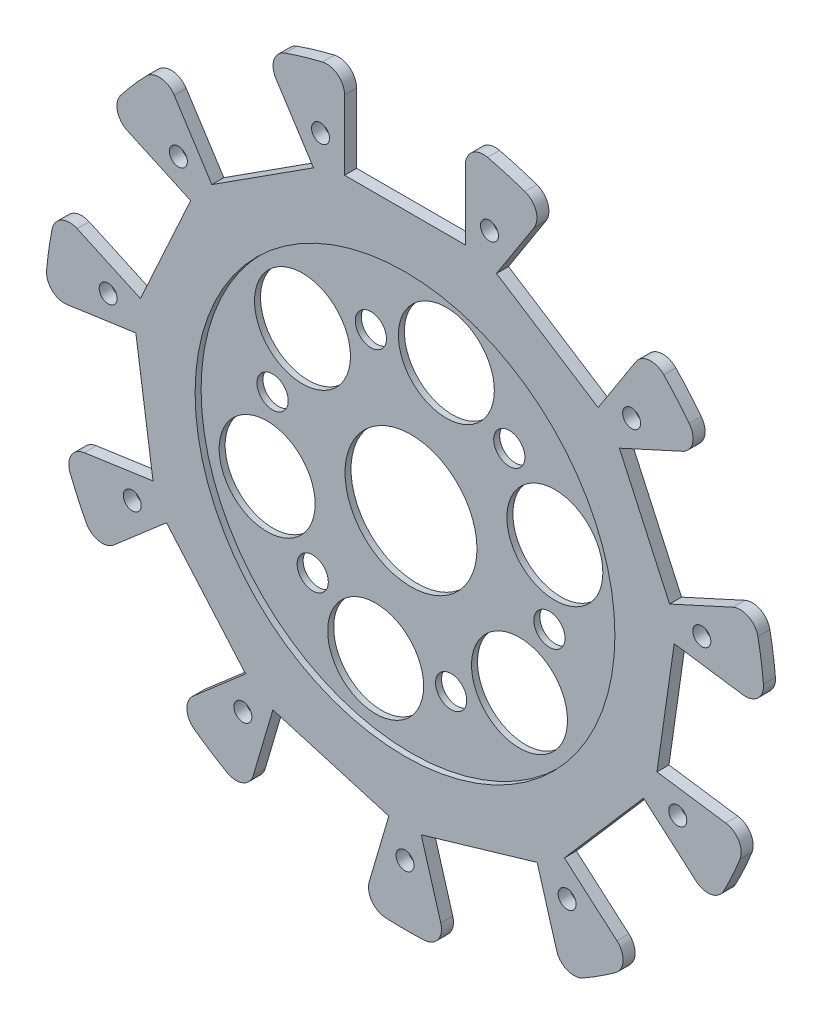
SolidWorks part; units mm, degrees
ref_plane "Front Plane" through (0, 0, 0) normal (0, 0, 1) x (1, 0, 0)
ref_plane "Top Plane" through (0, 0, 0) normal (0, 1, 0) x (1, 0, 0)
ref_plane "Right Plane" through (0, 0, 0) normal (1, 0, 0) x (0, 0, -1)
sketch "Sketch1" plane through (0, 0, 0) normal (0, 0, 1) x (1, 0, 0)
  line L44 (21.5207, 52.1193) -> (15.2567, 42.3722)
  line L47 (-10.0734, 55.4805) -> (-10.0734, 43.8941)
  line L48 (-10.0734, 43.8941) -> (10.0734, 43.8941)
  line L49 (10.0734, 55.4805) -> (10.0734, 43.8941)
  line L51 (38.4693, 41.2271) -> (32.2052, 31.48)
  line L52 (15.2567, 42.3722) -> (32.2052, 31.48)
  line L53 (46.2822, 32.2105) -> (35.7428, 27.3974)
  line L55 (54.6515, 13.8844) -> (44.1121, 9.0712)
  line L56 (35.7428, 27.3974) -> (44.1121, 9.0712)
  line L57 (56.3494, 2.0752) -> (44.8809, 3.7241)
  line L59 (53.4822, -17.8666) -> (42.0137, -16.2176)
  line L60 (44.8809, 3.7241) -> (42.0137, -16.2176)
  line L61 (48.526, -28.719) -> (39.7696, -21.1316)
  line L63 (35.3327, -43.945) -> (26.5763, -36.3575)
  line L64 (39.7696, -21.1316) -> (26.5763, -36.3575)
  line L65 (25.296, -50.3952) -> (22.0318, -39.2781)
  line L67 (5.9653, -56.0712) -> (2.701, -44.9541)
  line L68 (22.0318, -39.2781) -> (2.701, -44.9541)
  line L69 (-5.9653, -56.0712) -> (-2.701, -44.9541)
  line L71 (-25.296, -50.3952) -> (-22.0318, -39.2781)
  line L72 (-2.701, -44.9541) -> (-22.0318, -39.2781)
  line L73 (-35.3327, -43.945) -> (-26.5763, -36.3575)
  line L75 (-48.526, -28.719) -> (-39.7696, -21.1316)
  line L76 (-26.5763, -36.3575) -> (-39.7696, -21.1316)
  line L77 (-53.4822, -17.8666) -> (-42.0137, -16.2176)
  line L79 (-56.3494, 2.0752) -> (-44.8809, 3.7241)
  line L80 (-42.0137, -16.2176) -> (-44.8809, 3.7241)
  line L81 (-54.6515, 13.8844) -> (-44.1121, 9.0712)
  line L83 (-46.2822, 32.2105) -> (-35.7428, 27.3974)
  line L84 (-44.1121, 9.0712) -> (-35.7428, 27.3974)
  line L85 (-38.4693, 41.2271) -> (-32.2052, 31.48)
  line L87 (-21.5207, 52.1193) -> (-15.2567, 42.3722)
  line L88 (-32.2052, 31.48) -> (-15.2567, 42.3722)
  arc A33 (-43.1506, 41.6896) -> (-47.4063, 36.7783) centre (0, 0) ccw
  arc A34 (-13.7615, 58.4005) -> (-19.9968, 56.5697) centre (0, 0) ccw
  arc A35 (19.9968, 56.5697) -> (13.7615, 58.4005) centre (0, 0) ccw
  arc A36 (47.4063, 36.7783) -> (43.1506, 41.6896) centre (0, 0) ccw
  arc A37 (59.7646, 5.3101) -> (58.8397, 11.7426) centre (0, 0) ccw
  arc A38 (53.148, -27.844) -> (55.8476, -21.9327) centre (0, 0) ccw
  arc A39 (29.6574, -52.1578) -> (35.1243, -48.6444) centre (0, 0) ccw
  arc A40 (-3.2493, -59.912) -> (3.2493, -59.912) centre (0, 0) ccw
  arc A41 (-35.1243, -48.6444) -> (-29.6574, -52.1578) centre (0, 0) ccw
  arc A42 (-55.8476, -21.9327) -> (-53.148, -27.844) centre (0, 0) ccw
  arc A43 (-58.8397, 11.7426) -> (-59.7646, 5.3101) centre (0, 0) ccw
  arc A44 (-54.6515, 13.8844) -> (-58.8397, 11.7426) centre (-55.8977, 11.1555) ccw
  arc A45 (-56.3494, 2.0752) -> (-59.7646, 5.3101) centre (-56.7763, 5.0446) cw
  arc A46 (-48.526, -28.719) -> (-53.148, -27.844) centre (-50.4906, -26.4518) cw
  arc A47 (-53.4822, -17.8666) -> (-55.8476, -21.9327) centre (-53.0553, -20.836) ccw
  arc A48 (-25.296, -50.3952) -> (-29.6574, -52.1578) centre (-28.1745, -49.55) cw
  arc A49 (-35.3327, -43.945) -> (-35.1243, -48.6444) centre (-33.3681, -46.2122) ccw
  arc A50 (-5.9653, -56.0712) -> (-3.2493, -59.912) centre (-3.0868, -56.9164) ccw
  arc A51 (5.9653, -56.0712) -> (3.2493, -59.912) centre (3.0868, -56.9164) cw
  arc A52 (35.3327, -43.945) -> (35.1243, -48.6444) centre (33.3681, -46.2122) cw
  arc A53 (25.296, -50.3952) -> (29.6574, -52.1578) centre (28.1745, -49.55) ccw
  arc A54 (48.526, -28.719) -> (53.148, -27.844) centre (50.4906, -26.4518) ccw
  arc A55 (53.4822, -17.8666) -> (55.8476, -21.9327) centre (53.0553, -20.836) cw
  arc A56 (56.3494, 2.0752) -> (59.7646, 5.3101) centre (56.7763, 5.0446) ccw
  arc A57 (54.6515, 13.8844) -> (58.8397, 11.7426) centre (55.8977, 11.1555) cw
  arc A58 (46.2822, 32.2105) -> (47.4063, 36.7783) centre (45.036, 34.9394) ccw
  arc A59 (38.4693, 41.2271) -> (43.1506, 41.6896) centre (40.9931, 39.6052) cw
  arc A60 (21.5207, 52.1193) -> (19.9968, 56.5697) centre (18.997, 53.7412) ccw
  arc A61 (10.0734, 55.4805) -> (13.7615, 58.4005) centre (13.0734, 55.4805) cw
  arc A62 (-10.0734, 55.4805) -> (-13.7615, 58.4005) centre (-13.0734, 55.4805) ccw
  arc A63 (-21.5207, 52.1193) -> (-19.9968, 56.5697) centre (-18.997, 53.7412) cw
  arc A64 (-38.4693, 41.2271) -> (-43.1506, 41.6896) centre (-40.9931, 39.6052) ccw
  arc A65 (-46.2822, 32.2105) -> (-47.4063, 36.7783) centre (-45.036, 34.9394) cw
  point P3 (-57.9879, 15.408)
  point P51 (0, 0)
  point P55 (-57.1127, -18.3885)
  point P60 (-38.1047, -46.3469)
  point P63 (-6.9987, -59.5904)
  point P70 (26.3294, -53.9144)
  point P73 (51.298, -31.121)
  point P78 (59.9799, 1.5532)
  point P83 (49.6186, 33.7342)
  point P88 (23.5037, 55.2048)
  point P93 (-10.0734, 59.1483)
  dimension "D1" = 120
  dimension "D2" = 3
extrude "Boss-Extrude1" add sketch "Sketch1" along normal blind 2
sketch "Sketch2" plane through (0, 0, 2) normal (0, 0, 1) x (1, 0, 0)
  circle A0 centre (0, 0) radius 35
  dimension "D1" = 70
extrude "Cut-Extrude1" cut sketch "Sketch2" against normal blind 1
sketch "Sketch4" plane through (0, 0, 2) normal (0, 0, 1) x (1, 0, 0)
  line L0 (0, 17.7708) -> (0, 0) construction
  line L1 (0, 0) -> (-14.0866, 47.9746) construction
  circle A0 centre (-14.0866, 47.9746) radius 1.5
  circle A1 centre (14.0866, 47.9746) radius 1.5
  circle A2 centre (37.7875, 32.743) radius 1.5
  circle A3 centre (49.4911, 7.1157) radius 1.5
  circle A4 centre (45.4816, -20.7708) radius 1.5
  circle A5 centre (27.032, -42.0627) radius 1.5
  circle A6 centre (0, -50) radius 1.5
  circle A7 centre (-27.032, -42.0627) radius 1.5
  circle A8 centre (-45.4816, -20.7708) radius 1.5
  circle A9 centre (-49.4911, 7.1157) radius 1.5
  circle A10 centre (-37.7875, 32.743) radius 1.5
  point P28 (0, 0)
  dimension "D1" = 3
  dimension "D2" = 50
  dimension "D3" = 16.364
extrude "Cut-Extrude3" cut sketch "Sketch4" against normal blind 2
sketch "Sketch5" plane through (0, 0, 1) normal (0, 0, 1) x (1, 0, 0)
  line L0 (0, 0) -> (0, 11.9603) construction
  line L1 (0, 0) -> (-6.6911, 22.788) construction
  line L2 (0, 0) -> (-18.0934, 17.252) construction
  circle A0 centre (-6.6911, 22.788) radius 2.6
  circle A1 centre (-18.0934, 17.252) radius 8
  circle A2 centre (0, 0) radius 11
  circle A3 centre (16.3894, 17.1887) radius 2.6
  circle A4 centre (5.894, 24.2953) radius 8
  circle A5 centre (23.0805, -5.5993) radius 2.6
  circle A6 centre (23.9873, 7.0433) radius 8
  circle A7 centre (6.6911, -22.788) radius 2.6
  circle A8 centre (18.0934, -17.252) radius 8
  circle A9 centre (-16.3894, -17.1887) radius 2.6
  circle A10 centre (-5.894, -24.2953) radius 8
  circle A11 centre (-23.0805, 5.5993) radius 2.6
  circle A12 centre (-23.9873, -7.0433) radius 8
  point P31 (0, 0)
  dimension "D1" = 16
  dimension "D2" = 5.2
  dimension "D7" = 22
  dimension "D3" = 23.75
  dimension "D4" = 30
  dimension "D5" = 16.364
  dimension "D6" = 25
  dimension "D8" = 6
extrude "Cut-Extrude4" cut sketch "Sketch5" against normal blind 10
